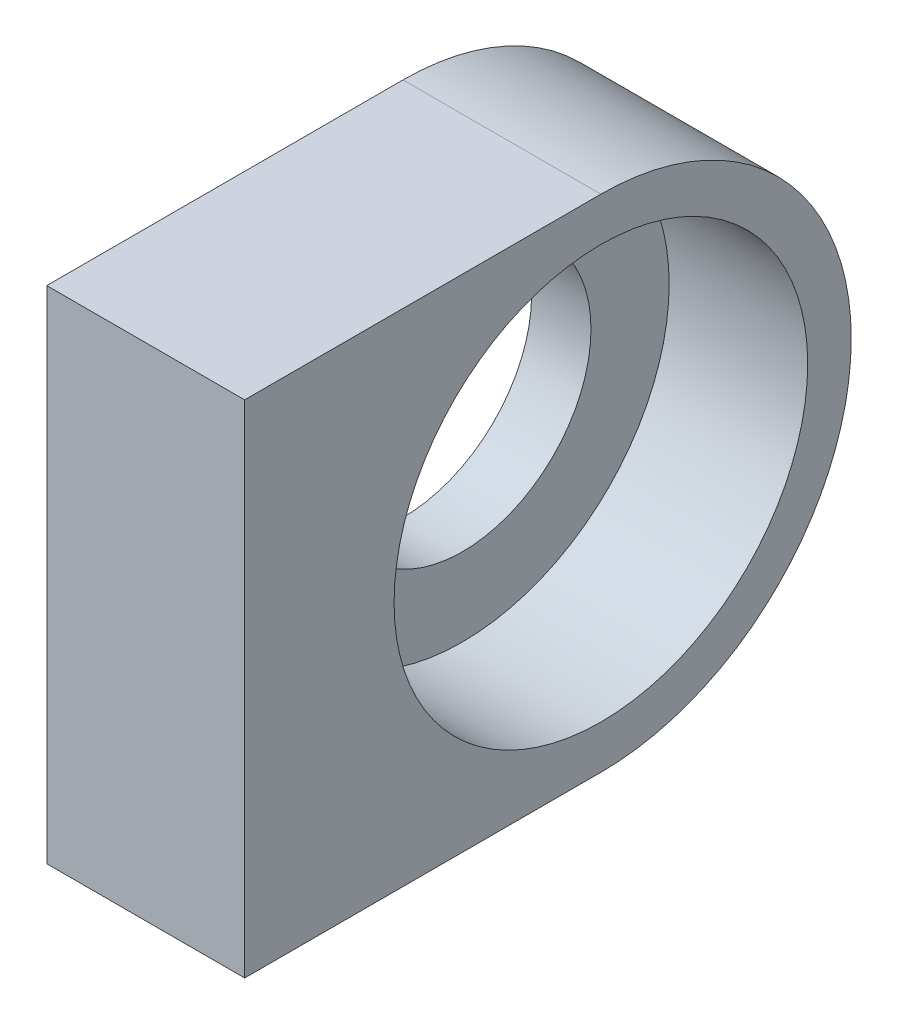
SolidWorks part; units mm, degrees
ref_plane "Front Plane" through (0, 0, 0) normal (1, 0, 0) x (0, 1, 0)
ref_plane "Top Plane" through (0, 0, 0) normal (0, 0, 1) x (0, 1, 0)
ref_plane "Right Plane" through (0, 0, 0) normal (0, 1, 0) x (-1, 0, 0)
sketch "Sketch1" plane through (0, 0, 0) normal (1, 0, 0) x (0, 1, 0)
  line L0 (-12.65, 0) -> (-12.65, 18)
  line L1 (12.65, 0) -> (12.65, 18)
  line L2 (-12.65, 18) -> (12.65, 18)
  line L3 (-12.65, 18) -> (12.65, 18) construction
  line L4 (0, 18) -> (0, -12.65) construction
  arc A2 (-12.65, 0) -> (12.65, 0) centre (0, 0) ccw
  point P11 (0, 15.0056)
  dimension "D1" = 25.3
extrude "Boss-Extrude1" add sketch "Sketch1" along normal blind 10
sketch "Sketch2" plane through (10, 0, 0) normal (1, 0, 0) x (0, 1, 0)
  circle A0 centre (0, 0) radius 10.45
  dimension "D1" = 20.9
extrude "Cut-Extrude1" cut sketch "Sketch2" against normal blind 7
sketch "Sketch3" plane through (3, 0, 0) normal (1, 0, 0) x (0, 1, 0)
  circle A0 centre (0, 0) radius 6.5
  dimension "D1" = 13
extrude "Cut-Extrude2" cut sketch "Sketch3" against normal through all
